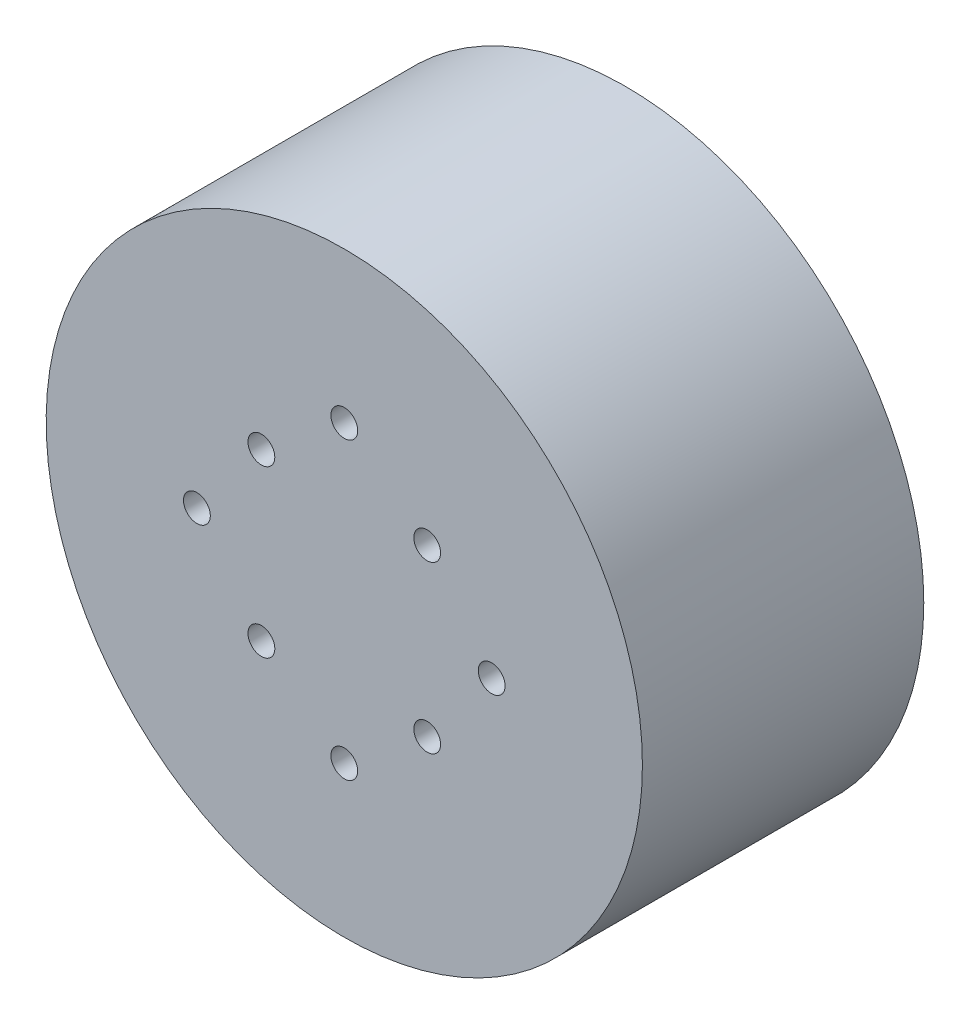
SolidWorks part; units mm, degrees
ref_plane "前视基准面" through (0, 0, 0) normal (0, 0, 1) x (1, 0, 0)
ref_plane "上视基准面" through (0, 0, 0) normal (0, 1, 0) x (1, 0, 0)
ref_plane "右视基准面" through (0, 0, 0) normal (1, 0, 0) x (0, 0, -1)
sketch "草图1" plane through (0, 0, 0) normal (0, 0, 1) x (1, 0, 0)
  circle A0 centre (0, 0) radius 44.5
  dimension "D1" = 89
extrude "凸台-拉伸1" add sketch "草图1" along normal blind 42
sketch "草图2" plane through (0, 0, 0) normal (0, 0, -1) x (-1, 0, 0)
  line L1 (-15, 15) -> (15, 15)
  line L2 (-15, 15) -> (-15, -15)
  line L3 (-15, -15) -> (15, -15)
  line L4 (15, 15) -> (15, -15)
  dimension "D1" = 30
  dimension "D2" = 15
  dimension "D3" = 15
hole_wizard "M4 螺纹孔的螺纹孔钻头1" positions "3D草图1" profile "草图3" hole size "M4" standard "GB"
sketch3d "3D草图1"
  point P0 (15, 15, 0)
  point P3 (-15, 15, 0)
  point P6 (-15, -15, 0)
  point P9 (15, -15, 0)
sketch "草图3" plane through (15, 15, 0) normal (1, 0, 0) x (0, 1, 0)
  line L0 (0, 0) -> (0, 12.9914)
  line L1 (0, 12.9914) -> (1.65, 12)
  line L2 (1.65, 12) -> (1.65, 0)
  line L5 (1.65, 0) -> (0, 0)
  line L10 (0, 12.9914) -> (-1.65, 12) construction
  line L11 (0, -6.35) -> (0, 107.95) construction
  dimension "孔直径" = 3.3
  dimension "孔深度" = 12
  dimension "导头角度" = 118
sketch "草图4" plane through (0, 0, 42) normal (0, 0, 1) x (1, 0, 0)
  line L0 (0, 0) -> (0, 20) construction
  line L1 (0, 0) -> (12.3744, 12.3744) construction
  circle A0 centre (0, 0) radius 22 construction
  circle A1 centre (0, 22) radius 2
  circle A2 centre (0, 0) radius 17.5 construction
  circle A3 centre (12.3744, 12.3744) radius 2
  dimension "D1" = 44
  dimension "D2" = 35
  dimension "D4" = 4
  dimension "D3" = 45
extrude "切除-拉伸1" cut sketch "草图4" against normal blind 10
pattern_circular "阵列(圆周)1" count 4 every 90 about axis through (0, 0, 0) along (0, 0, 1) of "切除-拉伸1"
sketch "草图5" plane through (0, 0, 0) normal (0, 0, -1) x (-1, 0, 0)
  line L1 (38.5047, -26.0166) -> (57.9829, -26.0166)
  line L2 (38.5047, -26.0166) -> (38.5047, 22.5308)
  line L3 (38.5047, 22.5308) -> (57.9829, 22.5308)
  line L4 (57.9829, -26.0166) -> (57.9829, 22.5308)
extrude "切除-拉伸2" cut sketch "草图5" against normal blind 10
sketch "草图6" plane through (-38.5047, 0, 0) normal (-1, 0, 0) x (0, 0, 1)
  line L1 (2.7128, -14.8532) -> (7.9581, -14.8532)
  line L2 (2.7128, -14.8532) -> (2.7128, 14.1993)
  line L3 (2.7128, 14.1993) -> (7.9581, 14.1993)
  line L4 (7.9581, -14.8532) -> (7.9581, 14.1993)
extrude "切除-拉伸3" cut sketch "草图6" against normal blind 10
